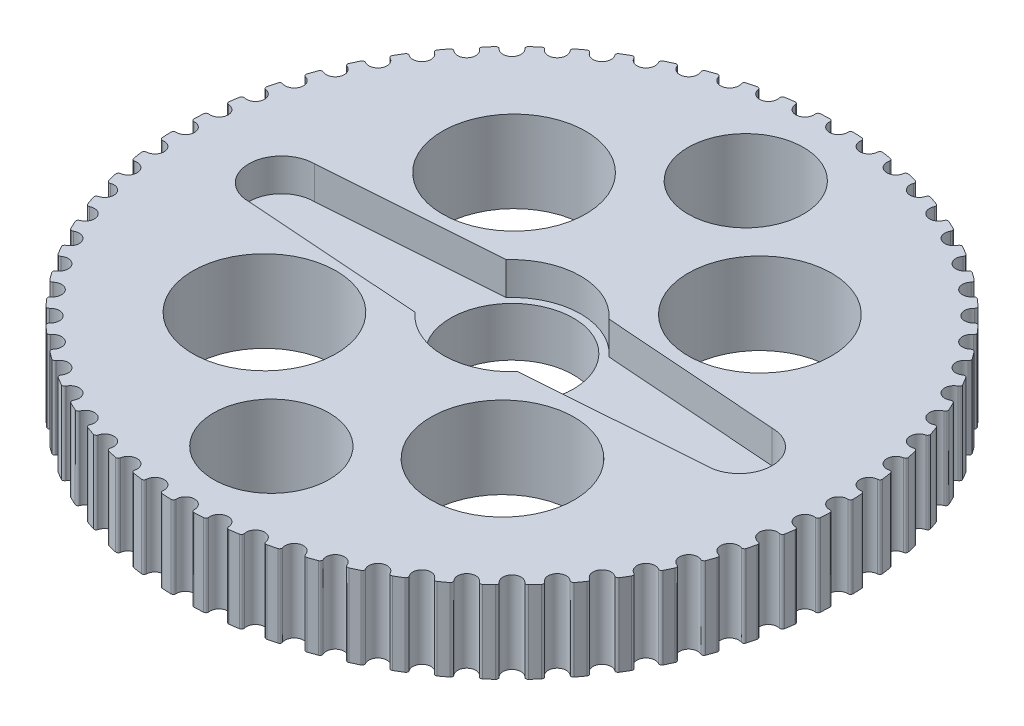
SolidWorks part; units mm, degrees
ref_plane "Front Plane" through (0, 0, 0) normal (0, 0, 1) x (1, 0, 0)
ref_plane "Top Plane" through (0, 0, 0) normal (0, 1, 0) x (1, 0, 0)
ref_plane "Right Plane" through (0, 0, 0) normal (1, 0, 0) x (0, 0, -1)
sketch "Sketch1" plane through (0, 0, 0) normal (0, 1, 0) x (1, 0, 0)
  line L1 (19.37, 0) -> (20.12, 0) construction
  arc A0 (1.2648, 20.0802) -> (0.7095, 20.1075) centre (0, 0) ccw
  arc A2 (0, 19.37) -> (0.5544, 19.9506) centre (0, 19.925) ccw
  arc A3 (1.4038, 19.9089) -> (1.8986, 19.2767) centre (1.953, 19.8291) ccw
  arc A4 (0.7095, 20.1075) -> (0.5544, 19.9506) centre (0.7042, 19.9576) ccw
  arc A5 (1.4038, 19.9089) -> (1.2648, 20.0802) centre (1.2553, 19.9305) ccw
  arc A6 (3.2269, 19.8595) -> (2.677, 19.9411) centre (0, 0) ccw
  arc A7 (1.8986, 19.2767) -> (2.5072, 19.8002) centre (1.953, 19.8291) ccw
  arc A8 (3.3484, 19.6755) -> (3.7789, 18.9978) centre (3.8872, 19.5421) ccw
  arc A9 (2.677, 19.9411) -> (2.5072, 19.8002) centre (2.657, 19.7924) ccw
  arc A10 (3.3484, 19.6755) -> (3.2269, 19.8595) centre (3.2028, 19.7115) ccw
  arc A11 (5.1579, 19.4476) -> (4.6187, 19.5827) centre (0, 0) ccw
  arc A12 (3.7789, 18.9978) -> (4.4359, 19.4591) centre (3.8872, 19.5421) ccw
  arc A13 (5.2608, 19.2525) -> (5.6228, 18.5359) centre (5.7839, 19.067) ccw
  arc A14 (4.6187, 19.5827) -> (4.4359, 19.4591) centre (4.5842, 19.4367) ccw
  arc A15 (5.2608, 19.2525) -> (5.1579, 19.4476) centre (5.1195, 19.3026) ccw
  arc A16 (7.0393, 18.8484) -> (6.5159, 19.0357) centre (0, 0) ccw
  arc A17 (5.6228, 18.5359) -> (6.3219, 18.9306) centre (5.7839, 19.067) ccw
  arc A18 (7.1226, 18.6442) -> (7.4126, 17.8955) centre (7.625, 18.4083) ccw
  arc A19 (6.5159, 19.0357) -> (6.3219, 18.9306) centre (6.4673, 18.8938) ccw
  arc A20 (7.1226, 18.6442) -> (7.0393, 18.8484) centre (6.9868, 18.7079) ccw
  arc A21 (8.8528, 18.0677) -> (8.3503, 18.3054) centre (0, 0) ccw
  arc A22 (7.4126, 17.8955) -> (8.147, 18.2198) centre (7.625, 18.4083) ccw
  arc A23 (8.9157, 17.8562) -> (9.131, 17.0828) centre (9.3926, 17.5723) ccw
  arc A24 (8.3503, 18.3054) -> (8.147, 18.2198) centre (8.2881, 18.1689) ccw
  arc A25 (8.9157, 17.8562) -> (8.8528, 18.0677) centre (8.7868, 17.933) ccw
  arc A26 (10.5812, 17.113) -> (10.1044, 17.3987) centre (0, 0) ccw
  arc A27 (9.131, 17.0828) -> (9.8936, 17.3336) centre (9.3926, 17.5723) ccw
  arc A28 (10.623, 16.8964) -> (10.7614, 16.1056) centre (11.0697, 16.567) ccw
  arc A29 (10.1044, 17.3987) -> (9.8936, 17.3336) centre (10.029, 17.269) ccw
  arc A30 (10.623, 16.8964) -> (10.5812, 17.113) centre (10.5023, 16.9854) ccw
  arc A31 (12.2076, 15.9934) -> (11.7611, 16.3246) centre (0, 0) ccw
  arc A32 (10.7614, 16.1056) -> (11.545, 16.2803) centre (11.0697, 16.567) ccw
  arc A33 (12.228, 15.7738) -> (12.2882, 14.9732) centre (12.6403, 15.4022) ccw
  arc A34 (11.7611, 16.3246) -> (11.545, 16.2803) centre (11.6734, 16.2029) ccw
  arc A35 (12.228, 15.7738) -> (12.2076, 15.9934) centre (12.1166, 15.8742) ccw
  arc A36 (13.7164, 14.7199) -> (13.3045, 15.0932) centre (0, 0) ccw
  arc A37 (12.2882, 14.9732) -> (13.0851, 15.0703) centre (12.6403, 15.4022) ccw
  arc A38 (13.7152, 14.4993) -> (13.6967, 13.6967) centre (14.0891, 14.0891) ccw
  arc A39 (13.3045, 15.0932) -> (13.0851, 15.0703) centre (13.2053, 14.9806) ccw
  arc A40 (13.7152, 14.4993) -> (13.7164, 14.7199) centre (13.6142, 14.6101) ccw
  arc A41 (15.0932, 13.3045) -> (14.7199, 13.7164) centre (0, 0) ccw
  arc A42 (13.6967, 13.6967) -> (14.4993, 13.7152) centre (14.0891, 14.0891) ccw
  arc A43 (15.0703, 13.0851) -> (14.9732, 12.2882) centre (15.4022, 12.6403) ccw
  arc A44 (14.7199, 13.7164) -> (14.4993, 13.7152) centre (14.6101, 13.6142) ccw
  arc A45 (15.0703, 13.0851) -> (15.0932, 13.3045) centre (14.9806, 13.2053) ccw
  arc A46 (16.3246, 11.7611) -> (15.9934, 12.2076) centre (0, 0) ccw
  arc A47 (14.9732, 12.2882) -> (15.7738, 12.228) centre (15.4022, 12.6403) ccw
  arc A48 (16.2803, 11.545) -> (16.1056, 10.7614) centre (16.567, 11.0697) ccw
  arc A49 (15.9934, 12.2076) -> (15.7738, 12.228) centre (15.8742, 12.1166) ccw
  arc A50 (16.2803, 11.545) -> (16.3246, 11.7611) centre (16.2029, 11.6734) ccw
  arc A51 (17.3987, 10.1044) -> (17.113, 10.5812) centre (0, 0) ccw
  arc A52 (16.1056, 10.7614) -> (16.8964, 10.623) centre (16.567, 11.0697) ccw
  arc A53 (17.3336, 9.8936) -> (17.0828, 9.131) centre (17.5723, 9.3926) ccw
  arc A54 (17.113, 10.5812) -> (16.8964, 10.623) centre (16.9854, 10.5023) ccw
  arc A55 (17.3336, 9.8936) -> (17.3987, 10.1044) centre (17.269, 10.029) ccw
  arc A56 (18.3054, 8.3503) -> (18.0677, 8.8528) centre (0, 0) ccw
  arc A57 (17.0828, 9.131) -> (17.8562, 8.9157) centre (17.5723, 9.3926) ccw
  arc A58 (18.2198, 8.147) -> (17.8955, 7.4126) centre (18.4083, 7.625) ccw
  arc A59 (18.0677, 8.8528) -> (17.8562, 8.9157) centre (17.933, 8.7868) ccw
  arc A60 (18.2198, 8.147) -> (18.3054, 8.3503) centre (18.1689, 8.2881) ccw
  arc A61 (19.0357, 6.5159) -> (18.8484, 7.0393) centre (0, 0) ccw
  arc A62 (17.8955, 7.4126) -> (18.6442, 7.1226) centre (18.4083, 7.625) ccw
  arc A63 (18.9306, 6.3219) -> (18.5359, 5.6228) centre (19.067, 5.7839) ccw
  arc A64 (18.8484, 7.0393) -> (18.6442, 7.1226) centre (18.7079, 6.9868) ccw
  arc A65 (18.9306, 6.3219) -> (19.0357, 6.5159) centre (18.8938, 6.4673) ccw
  arc A66 (19.5827, 4.6187) -> (19.4476, 5.1579) centre (0, 0) ccw
  arc A67 (18.5359, 5.6228) -> (19.2525, 5.2608) centre (19.067, 5.7839) ccw
  arc A68 (19.4591, 4.4359) -> (18.9978, 3.7789) centre (19.5421, 3.8872) ccw
  arc A69 (19.4476, 5.1579) -> (19.2525, 5.2608) centre (19.3026, 5.1195) ccw
  arc A70 (19.4591, 4.4359) -> (19.5827, 4.6187) centre (19.4367, 4.5842) ccw
  arc A71 (19.9411, 2.677) -> (19.8595, 3.2269) centre (0, 0) ccw
  arc A72 (18.9978, 3.7789) -> (19.6755, 3.3484) centre (19.5421, 3.8872) ccw
  arc A73 (19.8002, 2.5072) -> (19.2767, 1.8986) centre (19.8291, 1.953) ccw
  arc A74 (19.8595, 3.2269) -> (19.6755, 3.3484) centre (19.7115, 3.2028) ccw
  arc A75 (19.8002, 2.5072) -> (19.9411, 2.677) centre (19.7924, 2.657) ccw
  arc A76 (20.1075, 0.7095) -> (20.0802, 1.2648) centre (0, 0) ccw
  arc A77 (19.2767, 1.8986) -> (19.9089, 1.4038) centre (19.8291, 1.953) ccw
  arc A78 (19.9506, 0.5544) -> (19.37, 0) centre (19.925, 0) ccw
  arc A79 (20.0802, 1.2648) -> (19.9089, 1.4038) centre (19.9305, 1.2553) ccw
  arc A80 (19.9506, 0.5544) -> (20.1075, 0.7095) centre (19.9576, 0.7042) ccw
  arc A81 (20.0802, -1.2648) -> (20.1075, -0.7095) centre (0, 0) ccw
  arc A82 (19.37, 0) -> (19.9506, -0.5544) centre (19.925, 0) ccw
  arc A83 (19.9089, -1.4038) -> (19.2767, -1.8986) centre (19.8291, -1.953) ccw
  arc A84 (20.1075, -0.7095) -> (19.9506, -0.5544) centre (19.9576, -0.7042) ccw
  arc A85 (19.9089, -1.4038) -> (20.0802, -1.2648) centre (19.9305, -1.2553) ccw
  arc A86 (19.8595, -3.2269) -> (19.9411, -2.677) centre (0, 0) ccw
  arc A87 (19.2767, -1.8986) -> (19.8002, -2.5072) centre (19.8291, -1.953) ccw
  arc A88 (19.6755, -3.3484) -> (18.9978, -3.7789) centre (19.5421, -3.8872) ccw
  arc A89 (19.9411, -2.677) -> (19.8002, -2.5072) centre (19.7924, -2.657) ccw
  arc A90 (19.6755, -3.3484) -> (19.8595, -3.2269) centre (19.7115, -3.2028) ccw
  arc A91 (19.4476, -5.1579) -> (19.5827, -4.6187) centre (0, 0) ccw
  arc A92 (18.9978, -3.7789) -> (19.4591, -4.4359) centre (19.5421, -3.8872) ccw
  arc A93 (19.2525, -5.2608) -> (18.5359, -5.6228) centre (19.067, -5.7839) ccw
  arc A94 (19.5827, -4.6187) -> (19.4591, -4.4359) centre (19.4367, -4.5842) ccw
  arc A95 (19.2525, -5.2608) -> (19.4476, -5.1579) centre (19.3026, -5.1195) ccw
  arc A96 (18.8484, -7.0393) -> (19.0357, -6.5159) centre (0, 0) ccw
  arc A97 (18.5359, -5.6228) -> (18.9306, -6.3219) centre (19.067, -5.7839) ccw
  arc A98 (18.6442, -7.1226) -> (17.8955, -7.4126) centre (18.4083, -7.625) ccw
  arc A99 (19.0357, -6.5159) -> (18.9306, -6.3219) centre (18.8938, -6.4673) ccw
  arc A100 (18.6442, -7.1226) -> (18.8484, -7.0393) centre (18.7079, -6.9868) ccw
  arc A101 (18.0677, -8.8528) -> (18.3054, -8.3503) centre (0, 0) ccw
  arc A102 (17.8955, -7.4126) -> (18.2198, -8.147) centre (18.4083, -7.625) ccw
  arc A103 (17.8562, -8.9157) -> (17.0828, -9.131) centre (17.5723, -9.3926) ccw
  arc A104 (18.3054, -8.3503) -> (18.2198, -8.147) centre (18.1689, -8.2881) ccw
  arc A105 (17.8562, -8.9157) -> (18.0677, -8.8528) centre (17.933, -8.7868) ccw
  arc A106 (17.113, -10.5812) -> (17.3987, -10.1044) centre (0, 0) ccw
  arc A107 (17.0828, -9.131) -> (17.3336, -9.8936) centre (17.5723, -9.3926) ccw
  arc A108 (16.8964, -10.623) -> (16.1056, -10.7614) centre (16.567, -11.0697) ccw
  arc A109 (17.3987, -10.1044) -> (17.3336, -9.8936) centre (17.269, -10.029) ccw
  arc A110 (16.8964, -10.623) -> (17.113, -10.5812) centre (16.9854, -10.5023) ccw
  arc A111 (15.9934, -12.2076) -> (16.3246, -11.7611) centre (0, 0) ccw
  arc A112 (16.1056, -10.7614) -> (16.2803, -11.545) centre (16.567, -11.0697) ccw
  arc A113 (15.7738, -12.228) -> (14.9732, -12.2882) centre (15.4022, -12.6403) ccw
  arc A114 (16.3246, -11.7611) -> (16.2803, -11.545) centre (16.2029, -11.6734) ccw
  arc A115 (15.7738, -12.228) -> (15.9934, -12.2076) centre (15.8742, -12.1166) ccw
  arc A116 (14.7199, -13.7164) -> (15.0932, -13.3045) centre (0, 0) ccw
  arc A117 (14.9732, -12.2882) -> (15.0703, -13.0851) centre (15.4022, -12.6403) ccw
  arc A118 (14.4993, -13.7152) -> (13.6967, -13.6967) centre (14.0891, -14.0891) ccw
  arc A119 (15.0932, -13.3045) -> (15.0703, -13.0851) centre (14.9806, -13.2053) ccw
  arc A120 (14.4993, -13.7152) -> (14.7199, -13.7164) centre (14.6101, -13.6142) ccw
  arc A121 (13.3045, -15.0932) -> (13.7164, -14.7199) centre (0, 0) ccw
  arc A122 (13.6967, -13.6967) -> (13.7152, -14.4993) centre (14.0891, -14.0891) ccw
  arc A123 (13.0851, -15.0703) -> (12.2882, -14.9732) centre (12.6403, -15.4022) ccw
  arc A124 (13.7164, -14.7199) -> (13.7152, -14.4993) centre (13.6142, -14.6101) ccw
  arc A125 (13.0851, -15.0703) -> (13.3045, -15.0932) centre (13.2053, -14.9806) ccw
  arc A126 (11.7611, -16.3246) -> (12.2076, -15.9934) centre (0, 0) ccw
  arc A127 (12.2882, -14.9732) -> (12.228, -15.7738) centre (12.6403, -15.4022) ccw
  arc A128 (11.545, -16.2803) -> (10.7614, -16.1056) centre (11.0697, -16.567) ccw
  arc A129 (12.2076, -15.9934) -> (12.228, -15.7738) centre (12.1166, -15.8742) ccw
  arc A130 (11.545, -16.2803) -> (11.7611, -16.3246) centre (11.6734, -16.2029) ccw
  arc A131 (10.1044, -17.3987) -> (10.5812, -17.113) centre (0, 0) ccw
  arc A132 (10.7614, -16.1056) -> (10.623, -16.8964) centre (11.0697, -16.567) ccw
  arc A133 (9.8936, -17.3336) -> (9.131, -17.0828) centre (9.3926, -17.5723) ccw
  arc A134 (10.5812, -17.113) -> (10.623, -16.8964) centre (10.5023, -16.9854) ccw
  arc A135 (9.8936, -17.3336) -> (10.1044, -17.3987) centre (10.029, -17.269) ccw
  arc A136 (8.3503, -18.3054) -> (8.8528, -18.0677) centre (0, 0) ccw
  arc A137 (9.131, -17.0828) -> (8.9157, -17.8562) centre (9.3926, -17.5723) ccw
  arc A138 (8.147, -18.2198) -> (7.4126, -17.8955) centre (7.625, -18.4083) ccw
  arc A139 (8.8528, -18.0677) -> (8.9157, -17.8562) centre (8.7868, -17.933) ccw
  arc A140 (8.147, -18.2198) -> (8.3503, -18.3054) centre (8.2881, -18.1689) ccw
  arc A141 (6.5159, -19.0357) -> (7.0393, -18.8484) centre (0, 0) ccw
  arc A142 (7.4126, -17.8955) -> (7.1226, -18.6442) centre (7.625, -18.4083) ccw
  arc A143 (6.3219, -18.9306) -> (5.6228, -18.5359) centre (5.7839, -19.067) ccw
  arc A144 (7.0393, -18.8484) -> (7.1226, -18.6442) centre (6.9868, -18.7079) ccw
  arc A145 (6.3219, -18.9306) -> (6.5159, -19.0357) centre (6.4673, -18.8938) ccw
  arc A146 (4.6187, -19.5827) -> (5.1579, -19.4476) centre (0, 0) ccw
  arc A147 (5.6228, -18.5359) -> (5.2608, -19.2525) centre (5.7839, -19.067) ccw
  arc A148 (4.4359, -19.4591) -> (3.7789, -18.9978) centre (3.8872, -19.5421) ccw
  arc A149 (5.1579, -19.4476) -> (5.2608, -19.2525) centre (5.1195, -19.3026) ccw
  arc A150 (4.4359, -19.4591) -> (4.6187, -19.5827) centre (4.5842, -19.4367) ccw
  arc A151 (2.677, -19.9411) -> (3.2269, -19.8595) centre (0, 0) ccw
  arc A152 (3.7789, -18.9978) -> (3.3484, -19.6755) centre (3.8872, -19.5421) ccw
  arc A153 (2.5072, -19.8002) -> (1.8986, -19.2767) centre (1.953, -19.8291) ccw
  arc A154 (3.2269, -19.8595) -> (3.3484, -19.6755) centre (3.2028, -19.7115) ccw
  arc A155 (2.5072, -19.8002) -> (2.677, -19.9411) centre (2.657, -19.7924) ccw
  arc A156 (0.7095, -20.1075) -> (1.2648, -20.0802) centre (0, 0) ccw
  arc A157 (1.8986, -19.2767) -> (1.4038, -19.9089) centre (1.953, -19.8291) ccw
  arc A158 (0.5544, -19.9506) -> (0, -19.37) centre (0, -19.925) ccw
  arc A159 (1.2648, -20.0802) -> (1.4038, -19.9089) centre (1.2553, -19.9305) ccw
  arc A160 (0.5544, -19.9506) -> (0.7095, -20.1075) centre (0.7042, -19.9576) ccw
  arc A161 (-1.2648, -20.0802) -> (-0.7095, -20.1075) centre (0, 0) ccw
  arc A162 (0, -19.37) -> (-0.5544, -19.9506) centre (0, -19.925) ccw
  arc A163 (-1.4038, -19.9089) -> (-1.8986, -19.2767) centre (-1.953, -19.8291) ccw
  arc A164 (-0.7095, -20.1075) -> (-0.5544, -19.9506) centre (-0.7042, -19.9576) ccw
  arc A165 (-1.4038, -19.9089) -> (-1.2648, -20.0802) centre (-1.2553, -19.9305) ccw
  arc A166 (-3.2269, -19.8595) -> (-2.677, -19.9411) centre (0, 0) ccw
  arc A167 (-1.8986, -19.2767) -> (-2.5072, -19.8002) centre (-1.953, -19.8291) ccw
  arc A168 (-3.3484, -19.6755) -> (-3.7789, -18.9978) centre (-3.8872, -19.5421) ccw
  arc A169 (-2.677, -19.9411) -> (-2.5072, -19.8002) centre (-2.657, -19.7924) ccw
  arc A170 (-3.3484, -19.6755) -> (-3.2269, -19.8595) centre (-3.2028, -19.7115) ccw
  arc A171 (-5.1579, -19.4476) -> (-4.6187, -19.5827) centre (0, 0) ccw
  arc A172 (-3.7789, -18.9978) -> (-4.4359, -19.4591) centre (-3.8872, -19.5421) ccw
  arc A173 (-5.2608, -19.2525) -> (-5.6228, -18.5359) centre (-5.7839, -19.067) ccw
  arc A174 (-4.6187, -19.5827) -> (-4.4359, -19.4591) centre (-4.5842, -19.4367) ccw
  arc A175 (-5.2608, -19.2525) -> (-5.1579, -19.4476) centre (-5.1195, -19.3026) ccw
  arc A176 (-7.0393, -18.8484) -> (-6.5159, -19.0357) centre (0, 0) ccw
  arc A177 (-5.6228, -18.5359) -> (-6.3219, -18.9306) centre (-5.7839, -19.067) ccw
  arc A178 (-7.1226, -18.6442) -> (-7.4126, -17.8955) centre (-7.625, -18.4083) ccw
  arc A179 (-6.5159, -19.0357) -> (-6.3219, -18.9306) centre (-6.4673, -18.8938) ccw
  arc A180 (-7.1226, -18.6442) -> (-7.0393, -18.8484) centre (-6.9868, -18.7079) ccw
  arc A181 (-8.8528, -18.0677) -> (-8.3503, -18.3054) centre (0, 0) ccw
  arc A182 (-7.4126, -17.8955) -> (-8.147, -18.2198) centre (-7.625, -18.4083) ccw
  arc A183 (-8.9157, -17.8562) -> (-9.131, -17.0828) centre (-9.3926, -17.5723) ccw
  arc A184 (-8.3503, -18.3054) -> (-8.147, -18.2198) centre (-8.2881, -18.1689) ccw
  arc A185 (-8.9157, -17.8562) -> (-8.8528, -18.0677) centre (-8.7868, -17.933) ccw
  arc A186 (-10.5812, -17.113) -> (-10.1044, -17.3987) centre (0, 0) ccw
  arc A187 (-9.131, -17.0828) -> (-9.8936, -17.3336) centre (-9.3926, -17.5723) ccw
  arc A188 (-10.623, -16.8964) -> (-10.7614, -16.1056) centre (-11.0697, -16.567) ccw
  arc A189 (-10.1044, -17.3987) -> (-9.8936, -17.3336) centre (-10.029, -17.269) ccw
  arc A190 (-10.623, -16.8964) -> (-10.5812, -17.113) centre (-10.5023, -16.9854) ccw
  arc A191 (-12.2076, -15.9934) -> (-11.7611, -16.3246) centre (0, 0) ccw
  arc A192 (-10.7614, -16.1056) -> (-11.545, -16.2803) centre (-11.0697, -16.567) ccw
  arc A193 (-12.228, -15.7738) -> (-12.2882, -14.9732) centre (-12.6403, -15.4022) ccw
  arc A194 (-11.7611, -16.3246) -> (-11.545, -16.2803) centre (-11.6734, -16.2029) ccw
  arc A195 (-12.228, -15.7738) -> (-12.2076, -15.9934) centre (-12.1166, -15.8742) ccw
  arc A196 (-13.7164, -14.7199) -> (-13.3045, -15.0932) centre (0, 0) ccw
  arc A197 (-12.2882, -14.9732) -> (-13.0851, -15.0703) centre (-12.6403, -15.4022) ccw
  arc A198 (-13.7152, -14.4993) -> (-13.6967, -13.6967) centre (-14.0891, -14.0891) ccw
  arc A199 (-13.3045, -15.0932) -> (-13.0851, -15.0703) centre (-13.2053, -14.9806) ccw
  arc A200 (-13.7152, -14.4993) -> (-13.7164, -14.7199) centre (-13.6142, -14.6101) ccw
  arc A201 (-15.0932, -13.3045) -> (-14.7199, -13.7164) centre (0, 0) ccw
  arc A202 (-13.6967, -13.6967) -> (-14.4993, -13.7152) centre (-14.0891, -14.0891) ccw
  arc A203 (-15.0703, -13.0851) -> (-14.9732, -12.2882) centre (-15.4022, -12.6403) ccw
  arc A204 (-14.7199, -13.7164) -> (-14.4993, -13.7152) centre (-14.6101, -13.6142) ccw
  arc A205 (-15.0703, -13.0851) -> (-15.0932, -13.3045) centre (-14.9806, -13.2053) ccw
  arc A206 (-16.3246, -11.7611) -> (-15.9934, -12.2076) centre (0, 0) ccw
  arc A207 (-14.9732, -12.2882) -> (-15.7738, -12.228) centre (-15.4022, -12.6403) ccw
  arc A208 (-16.2803, -11.545) -> (-16.1056, -10.7614) centre (-16.567, -11.0697) ccw
  arc A209 (-15.9934, -12.2076) -> (-15.7738, -12.228) centre (-15.8742, -12.1166) ccw
  arc A210 (-16.2803, -11.545) -> (-16.3246, -11.7611) centre (-16.2029, -11.6734) ccw
  arc A211 (-17.3987, -10.1044) -> (-17.113, -10.5812) centre (0, 0) ccw
  arc A212 (-16.1056, -10.7614) -> (-16.8964, -10.623) centre (-16.567, -11.0697) ccw
  arc A213 (-17.3336, -9.8936) -> (-17.0828, -9.131) centre (-17.5723, -9.3926) ccw
  arc A214 (-17.113, -10.5812) -> (-16.8964, -10.623) centre (-16.9854, -10.5023) ccw
  arc A215 (-17.3336, -9.8936) -> (-17.3987, -10.1044) centre (-17.269, -10.029) ccw
  arc A216 (-18.3054, -8.3503) -> (-18.0677, -8.8528) centre (0, 0) ccw
  arc A217 (-17.0828, -9.131) -> (-17.8562, -8.9157) centre (-17.5723, -9.3926) ccw
  arc A218 (-18.2198, -8.147) -> (-17.8955, -7.4126) centre (-18.4083, -7.625) ccw
  arc A219 (-18.0677, -8.8528) -> (-17.8562, -8.9157) centre (-17.933, -8.7868) ccw
  arc A220 (-18.2198, -8.147) -> (-18.3054, -8.3503) centre (-18.1689, -8.2881) ccw
  arc A221 (-19.0357, -6.5159) -> (-18.8484, -7.0393) centre (0, 0) ccw
  arc A222 (-17.8955, -7.4126) -> (-18.6442, -7.1226) centre (-18.4083, -7.625) ccw
  arc A223 (-18.9306, -6.3219) -> (-18.5359, -5.6228) centre (-19.067, -5.7839) ccw
  arc A224 (-18.8484, -7.0393) -> (-18.6442, -7.1226) centre (-18.7079, -6.9868) ccw
  arc A225 (-18.9306, -6.3219) -> (-19.0357, -6.5159) centre (-18.8938, -6.4673) ccw
  arc A226 (-19.5827, -4.6187) -> (-19.4476, -5.1579) centre (0, 0) ccw
  arc A227 (-18.5359, -5.6228) -> (-19.2525, -5.2608) centre (-19.067, -5.7839) ccw
  arc A228 (-19.4591, -4.4359) -> (-18.9978, -3.7789) centre (-19.5421, -3.8872) ccw
  arc A229 (-19.4476, -5.1579) -> (-19.2525, -5.2608) centre (-19.3026, -5.1195) ccw
  arc A230 (-19.4591, -4.4359) -> (-19.5827, -4.6187) centre (-19.4367, -4.5842) ccw
  arc A231 (-19.9411, -2.677) -> (-19.8595, -3.2269) centre (0, 0) ccw
  arc A232 (-18.9978, -3.7789) -> (-19.6755, -3.3484) centre (-19.5421, -3.8872) ccw
  arc A233 (-19.8002, -2.5072) -> (-19.2767, -1.8986) centre (-19.8291, -1.953) ccw
  arc A234 (-19.8595, -3.2269) -> (-19.6755, -3.3484) centre (-19.7115, -3.2028) ccw
  arc A235 (-19.8002, -2.5072) -> (-19.9411, -2.677) centre (-19.7924, -2.657) ccw
  arc A236 (-20.1075, -0.7095) -> (-20.0802, -1.2648) centre (0, 0) ccw
  arc A237 (-19.2767, -1.8986) -> (-19.9089, -1.4038) centre (-19.8291, -1.953) ccw
  arc A238 (-19.9506, -0.5544) -> (-19.37, 0) centre (-19.925, 0) ccw
  arc A239 (-20.0802, -1.2648) -> (-19.9089, -1.4038) centre (-19.9305, -1.2553) ccw
  arc A240 (-19.9506, -0.5544) -> (-20.1075, -0.7095) centre (-19.9576, -0.7042) ccw
  arc A241 (-20.0802, 1.2648) -> (-20.1075, 0.7095) centre (0, 0) ccw
  arc A242 (-19.37, 0) -> (-19.9506, 0.5544) centre (-19.925, 0) ccw
  arc A243 (-19.9089, 1.4038) -> (-19.2767, 1.8986) centre (-19.8291, 1.953) ccw
  arc A244 (-20.1075, 0.7095) -> (-19.9506, 0.5544) centre (-19.9576, 0.7042) ccw
  arc A245 (-19.9089, 1.4038) -> (-20.0802, 1.2648) centre (-19.9305, 1.2553) ccw
  arc A246 (-19.8595, 3.2269) -> (-19.9411, 2.677) centre (0, 0) ccw
  arc A247 (-19.2767, 1.8986) -> (-19.8002, 2.5072) centre (-19.8291, 1.953) ccw
  arc A248 (-19.6755, 3.3484) -> (-18.9978, 3.7789) centre (-19.5421, 3.8872) ccw
  arc A249 (-19.9411, 2.677) -> (-19.8002, 2.5072) centre (-19.7924, 2.657) ccw
  arc A250 (-19.6755, 3.3484) -> (-19.8595, 3.2269) centre (-19.7115, 3.2028) ccw
  arc A251 (-19.4476, 5.1579) -> (-19.5827, 4.6187) centre (0, 0) ccw
  arc A252 (-18.9978, 3.7789) -> (-19.4591, 4.4359) centre (-19.5421, 3.8872) ccw
  arc A253 (-19.2525, 5.2608) -> (-18.5359, 5.6228) centre (-19.067, 5.7839) ccw
  arc A254 (-19.5827, 4.6187) -> (-19.4591, 4.4359) centre (-19.4367, 4.5842) ccw
  arc A255 (-19.2525, 5.2608) -> (-19.4476, 5.1579) centre (-19.3026, 5.1195) ccw
  arc A256 (-18.8484, 7.0393) -> (-19.0357, 6.5159) centre (0, 0) ccw
  arc A257 (-18.5359, 5.6228) -> (-18.9306, 6.3219) centre (-19.067, 5.7839) ccw
  arc A258 (-18.6442, 7.1226) -> (-17.8955, 7.4126) centre (-18.4083, 7.625) ccw
  arc A259 (-19.0357, 6.5159) -> (-18.9306, 6.3219) centre (-18.8938, 6.4673) ccw
  arc A260 (-18.6442, 7.1226) -> (-18.8484, 7.0393) centre (-18.7079, 6.9868) ccw
  arc A261 (-18.0677, 8.8528) -> (-18.3054, 8.3503) centre (0, 0) ccw
  arc A262 (-17.8955, 7.4126) -> (-18.2198, 8.147) centre (-18.4083, 7.625) ccw
  arc A263 (-17.8562, 8.9157) -> (-17.0828, 9.131) centre (-17.5723, 9.3926) ccw
  arc A264 (-18.3054, 8.3503) -> (-18.2198, 8.147) centre (-18.1689, 8.2881) ccw
  arc A265 (-17.8562, 8.9157) -> (-18.0677, 8.8528) centre (-17.933, 8.7868) ccw
  arc A266 (-17.113, 10.5812) -> (-17.3987, 10.1044) centre (0, 0) ccw
  arc A267 (-17.0828, 9.131) -> (-17.3336, 9.8936) centre (-17.5723, 9.3926) ccw
  arc A268 (-16.8964, 10.623) -> (-16.1056, 10.7614) centre (-16.567, 11.0697) ccw
  arc A269 (-17.3987, 10.1044) -> (-17.3336, 9.8936) centre (-17.269, 10.029) ccw
  arc A270 (-16.8964, 10.623) -> (-17.113, 10.5812) centre (-16.9854, 10.5023) ccw
  arc A271 (-15.9934, 12.2076) -> (-16.3246, 11.7611) centre (0, 0) ccw
  arc A272 (-16.1056, 10.7614) -> (-16.2803, 11.545) centre (-16.567, 11.0697) ccw
  arc A273 (-15.7738, 12.228) -> (-14.9732, 12.2882) centre (-15.4022, 12.6403) ccw
  arc A274 (-16.3246, 11.7611) -> (-16.2803, 11.545) centre (-16.2029, 11.6734) ccw
  arc A275 (-15.7738, 12.228) -> (-15.9934, 12.2076) centre (-15.8742, 12.1166) ccw
  arc A276 (-14.7199, 13.7164) -> (-15.0932, 13.3045) centre (0, 0) ccw
  arc A277 (-14.9732, 12.2882) -> (-15.0703, 13.0851) centre (-15.4022, 12.6403) ccw
  arc A278 (-14.4993, 13.7152) -> (-13.6967, 13.6967) centre (-14.0891, 14.0891) ccw
  arc A279 (-15.0932, 13.3045) -> (-15.0703, 13.0851) centre (-14.9806, 13.2053) ccw
  arc A280 (-14.4993, 13.7152) -> (-14.7199, 13.7164) centre (-14.6101, 13.6142) ccw
  arc A281 (-13.3045, 15.0932) -> (-13.7164, 14.7199) centre (0, 0) ccw
  arc A282 (-13.6967, 13.6967) -> (-13.7152, 14.4993) centre (-14.0891, 14.0891) ccw
  arc A283 (-13.0851, 15.0703) -> (-12.2882, 14.9732) centre (-12.6403, 15.4022) ccw
  arc A284 (-13.7164, 14.7199) -> (-13.7152, 14.4993) centre (-13.6142, 14.6101) ccw
  arc A285 (-13.0851, 15.0703) -> (-13.3045, 15.0932) centre (-13.2053, 14.9806) ccw
  arc A286 (-11.7611, 16.3246) -> (-12.2076, 15.9934) centre (0, 0) ccw
  arc A287 (-12.2882, 14.9732) -> (-12.228, 15.7738) centre (-12.6403, 15.4022) ccw
  arc A288 (-11.545, 16.2803) -> (-10.7614, 16.1056) centre (-11.0697, 16.567) ccw
  arc A289 (-12.2076, 15.9934) -> (-12.228, 15.7738) centre (-12.1166, 15.8742) ccw
  arc A290 (-11.545, 16.2803) -> (-11.7611, 16.3246) centre (-11.6734, 16.2029) ccw
  arc A291 (-10.1044, 17.3987) -> (-10.5812, 17.113) centre (0, 0) ccw
  arc A292 (-10.7614, 16.1056) -> (-10.623, 16.8964) centre (-11.0697, 16.567) ccw
  arc A293 (-9.8936, 17.3336) -> (-9.131, 17.0828) centre (-9.3926, 17.5723) ccw
  arc A294 (-10.5812, 17.113) -> (-10.623, 16.8964) centre (-10.5023, 16.9854) ccw
  arc A295 (-9.8936, 17.3336) -> (-10.1044, 17.3987) centre (-10.029, 17.269) ccw
  arc A296 (-8.3503, 18.3054) -> (-8.8528, 18.0677) centre (0, 0) ccw
  arc A297 (-9.131, 17.0828) -> (-8.9157, 17.8562) centre (-9.3926, 17.5723) ccw
  arc A298 (-8.147, 18.2198) -> (-7.4126, 17.8955) centre (-7.625, 18.4083) ccw
  arc A299 (-8.8528, 18.0677) -> (-8.9157, 17.8562) centre (-8.7868, 17.933) ccw
  arc A300 (-8.147, 18.2198) -> (-8.3503, 18.3054) centre (-8.2881, 18.1689) ccw
  arc A301 (-6.5159, 19.0357) -> (-7.0393, 18.8484) centre (0, 0) ccw
  arc A302 (-7.4126, 17.8955) -> (-7.1226, 18.6442) centre (-7.625, 18.4083) ccw
  arc A303 (-6.3219, 18.9306) -> (-5.6228, 18.5359) centre (-5.7839, 19.067) ccw
  arc A304 (-7.0393, 18.8484) -> (-7.1226, 18.6442) centre (-6.9868, 18.7079) ccw
  arc A305 (-6.3219, 18.9306) -> (-6.5159, 19.0357) centre (-6.4673, 18.8938) ccw
  arc A306 (-4.6187, 19.5827) -> (-5.1579, 19.4476) centre (0, 0) ccw
  arc A307 (-5.6228, 18.5359) -> (-5.2608, 19.2525) centre (-5.7839, 19.067) ccw
  arc A308 (-4.4359, 19.4591) -> (-3.7789, 18.9978) centre (-3.8872, 19.5421) ccw
  arc A309 (-5.1579, 19.4476) -> (-5.2608, 19.2525) centre (-5.1195, 19.3026) ccw
  arc A310 (-4.4359, 19.4591) -> (-4.6187, 19.5827) centre (-4.5842, 19.4367) ccw
  arc A311 (-2.677, 19.9411) -> (-3.2269, 19.8595) centre (0, 0) ccw
  arc A312 (-3.7789, 18.9978) -> (-3.3484, 19.6755) centre (-3.8872, 19.5421) ccw
  arc A313 (-2.5072, 19.8002) -> (-1.8986, 19.2767) centre (-1.953, 19.8291) ccw
  arc A314 (-3.2269, 19.8595) -> (-3.3484, 19.6755) centre (-3.2028, 19.7115) ccw
  arc A315 (-2.5072, 19.8002) -> (-2.677, 19.9411) centre (-2.657, 19.7924) ccw
  arc A316 (-0.7095, 20.1075) -> (-1.2648, 20.0802) centre (0, 0) ccw
  arc A317 (-1.8986, 19.2767) -> (-1.4038, 19.9089) centre (-1.953, 19.8291) ccw
  arc A318 (-0.5544, 19.9506) -> (0, 19.37) centre (0, 19.925) ccw
  arc A319 (-1.2648, 20.0802) -> (-1.4038, 19.9089) centre (-1.2553, 19.9305) ccw
  arc A320 (-0.5544, 19.9506) -> (-0.7095, 20.1075) centre (-0.7042, 19.9576) ccw
extrude "Boss-Extrude1" add sketch "Sketch1" along normal blind 5
sketch "Sketch2" plane through (0, 5, 0) normal (0, 1, 0) x (1, 0, 0)
  line L4 (-3.1413, -2.7756) -> (-14.0585, -2)
  line L5 (3.1361, 2.7814) -> (13.8624, 2)
  line L6 (3.1413, -2.7756) -> (13.8624, -2)
  line L7 (-3.1361, 2.7814) -> (-14.0585, 2)
  arc A0 (-3.1413, -2.7756) -> (3.1413, -2.7756) centre (0, 0) ccw
  arc A2 (13.8624, -2) -> (13.8624, 2) centre (13.8624, 0) ccw
  arc A3 (-14.0585, -2) -> (-14.0585, 2) centre (-14.0585, 0) cw
  arc A4 (3.1361, 2.7814) -> (-3.1361, 2.7814) centre (0, 0) ccw
extrude "Cut-Extrude2" cut sketch "Sketch2" against normal blind 2
sketch "Sketch4" plane through (0, 3, 0) normal (0, 1, 0) x (1, 0, 0)
  circle A0 centre (0, 0) radius 3.75
extrude "Cut-Extrude3" cut sketch "Sketch4" against normal blind 3
sketch "Sketch5" plane through (0, 5, 0) normal (0, 1, 0) x (1, 0, 0)
  line L1 (-17.705, 0.2838) -> (18.6734, -0.2827) construction
  line L2 (0, 17.9126) -> (0, -18.1006) construction
  circle A0 centre (-7.5, 7.6258) radius 4.3768
  circle A1 centre (7.5, 7.6258) radius 4.3768
  circle A2 centre (7.2592, -7.8395) radius 4.3768
  circle A3 centre (-7.7336, -7.3724) radius 4.3768
  circle A4 centre (0, 14.265) radius 3.5248
  circle A5 centre (-0.4439, -14.2419) radius 3.5248
  dimension "D1" = 7.5
  dimension "D2" = 7.5
extrude "Cut-Extrude4" cut sketch "Sketch5" against normal through all
